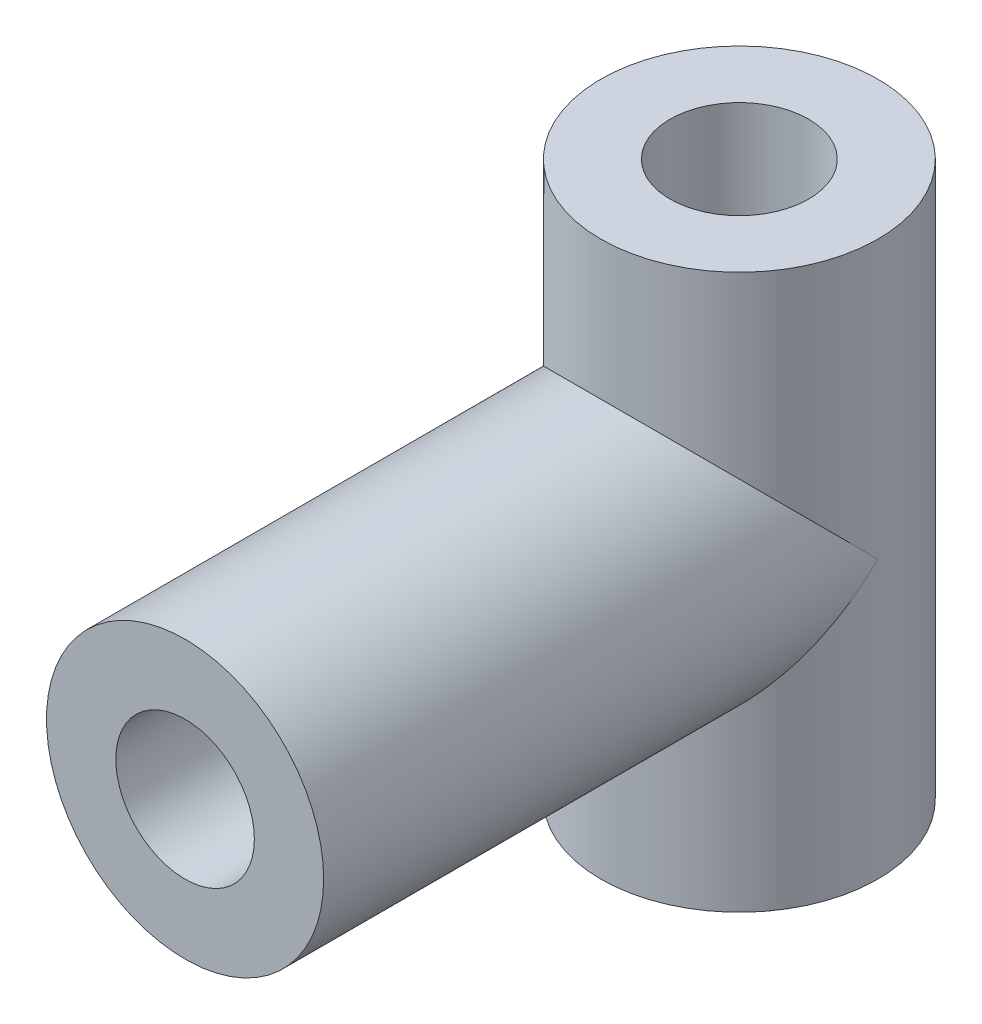
SolidWorks part; units mm, degrees
ref_plane "前基準面" through (0, 0, 0) normal (0, 0, 1) x (1, 0, 0)
ref_plane "上基準面" through (0, 0, 0) normal (0, 1, 0) x (1, 0, 0)
ref_plane "右基準面" through (0, 0, 0) normal (1, 0, 0) x (0, 0, -1)
sketch "草圖1" plane through (0, 0, 0) normal (0, 1, 0) x (1, 0, 0)
  circle A0 centre (0, 0) radius 5
  dimension "D1" = 10
extrude "填料-伸長1" add sketch "草圖1" along normal mid plane 20
sketch "草圖2" plane through (0, 0, 0) normal (0, 0, 1) x (1, 0, 0)
  line L0 (-5, 10) -> (-5, -10) construction
  line L1 (5, -10) -> (5, 10) construction
  line L2 (-5, 10) -> (-5, -10) construction
  line L3 (5, -10) -> (5, 10) construction
  line L4 (-5, 0) -> (5, 0) construction
  circle A0 centre (0, 0) radius 5
  point P9 (0, 0)
extrude "填料-伸長2" add sketch "草圖2" along normal blind 20
sketch "草圖3" plane through (0, 0, 20) normal (0, 0, 1) x (1, 0, 0)
  circle A0 centre (0, 0) radius 2.5
  dimension "D1" = 5
extrude "除料-伸長1" cut sketch "草圖3" against normal blind 15
sketch "草圖4" plane through (0, -10, 0) normal (0, -1, 0) x (1, 0, 0)
  circle A0 centre (0, 0) radius 2.5
  dimension "D1" = 5
extrude "除料-伸長2" cut sketch "草圖4" against normal through all
